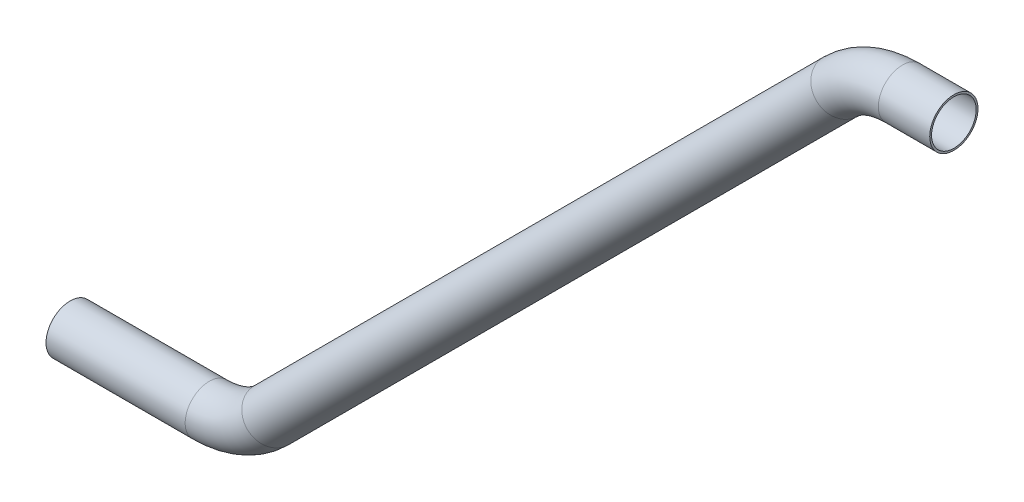
SolidWorks part; units mm, degrees
ref_plane "Front" through (0, 0, 0) normal (0, 0, 1) x (1, 0, 0)
ref_plane "Top" through (0, 0, 0) normal (0, 1, 0) x (1, 0, 0)
ref_plane "Right" through (0, 0, 0) normal (1, 0, 0) x (0, 0, -1)
sketch "Croquis1" plane through (0, 0, 0) normal (0, 0, 1) x (1, 0, 0)
  line L0 (0, 0) -> (237.868, 0)
  line L1 (343.934, 43.934) -> (1316.7262, 1016.7262)
  line L2 (1422.7922, 1060.6602) -> (1510.6602, 1060.6602)
  arc A0 (237.868, 0) -> (343.934, 43.934) centre (237.868, 150) ccw
  arc A1 (1316.7262, 1016.7262) -> (1422.7922, 1060.6602) centre (1422.7922, 910.6602) cw
  point P7 (300, 0)
  point P10 (1360.6602, 1060.6602)
  dimension "D5" = 150
  dimension "D1" = 45
  dimension "D2" = 1500
  dimension "D3" = 300
  dimension "D4" = 150
sweep "Barrer2" add path "Croquis1" circular profile diameter 82.55 parameters "D3"=82.55
shell "Vaciado1" thickness 3.175
equation "\"Largo\"= 1500mm"
equation "\"D2@Croquis1\"=\"Largo\""
